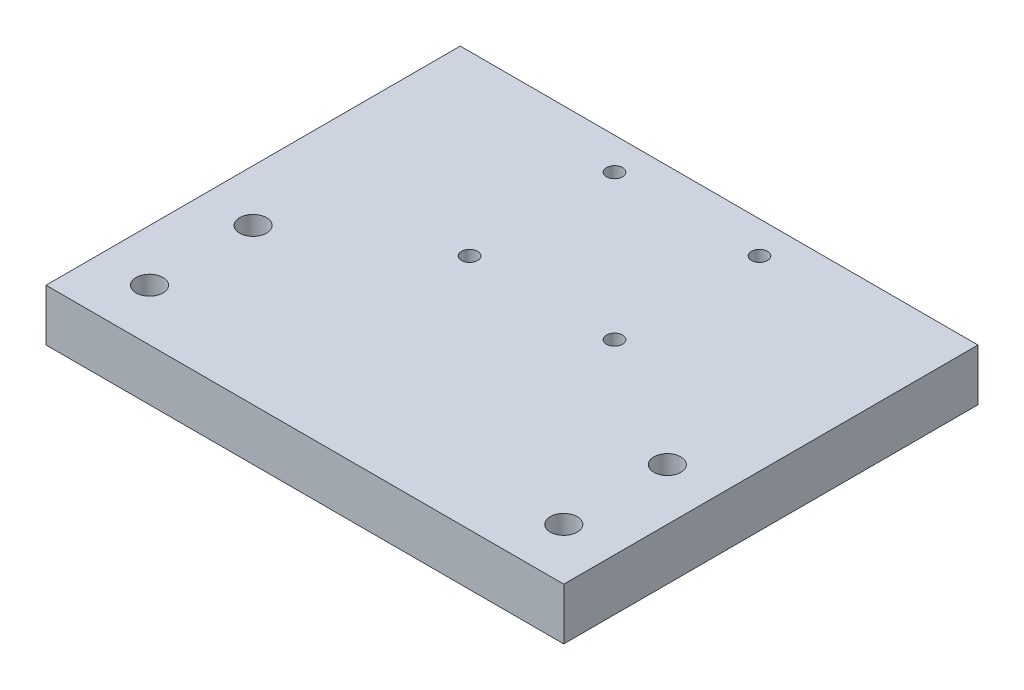
SolidWorks part; units mm, degrees
ref_plane "前视基准面" through (0, 0, 0) normal (0, 0, 1) x (1, 0, 0)
ref_plane "上视基准面" through (0, 0, 0) normal (0, 1, 0) x (1, 0, 0)
ref_plane "右视基准面" through (0, 0, 0) normal (1, 0, 0) x (0, 0, -1)
other "Configuration Table"
sketch "草图1" plane through (0, 0, 0) normal (0, 1, 0) x (1, 0, 0)
  line L1 (-50, 40) -> (50, 40)
  line L2 (-50, 40) -> (-50, -40)
  line L3 (-50, -40) -> (50, -40)
  line L4 (50, 40) -> (50, -40)
  line L5 (-50, 40) -> (50, -40) construction
  line L6 (-50, -40) -> (50, 40) construction
  point P0 (0, 0)
  dimension "D1" = 80
  dimension "D2" = 100
extrude "凸台-拉伸1" add sketch "草图1" along normal blind 10
sketch "草图3" plane through (0, 0, 0) normal (0, -1, 0) x (1, 0, 0)
  circle A0 centre (40, 30) radius 2.6
  circle A1 centre (40, 10) radius 2.6
  circle A2 centre (-40, 30) radius 2.6
  circle A3 centre (-40, 10) radius 2.6
  dimension "D1" = 5.2
  dimension "D2" = 5.2
  dimension "D3" = 5.2
  dimension "D4" = 5.2
extrude "切除-拉伸2" cut sketch "草图3" against normal through all
cosmetic thread "装饰螺纹线1" parameters "D1"=10, "D2"=6.2
cosmetic thread "装饰螺纹线2" parameters "D1"=10, "D2"=6.2
cosmetic thread "装饰螺纹线3" parameters "D1"=10, "D2"=6.2
cosmetic thread "装饰螺纹线4" parameters "D1"=10, "D2"=6.2
sketch "草图4" plane through (0, 10, 0) normal (0, 1, 0) x (1, 0, 0)
  circle A0 centre (14, 33.8) radius 1.55
  circle A1 centre (14, 5.8) radius 1.55
  circle A2 centre (-14, 33.8) radius 1.55
  circle A3 centre (-14, 5.8) radius 1.55
  dimension "D1" = 3.1
  dimension "D2" = 3.1
  dimension "D3" = 3.1
  dimension "D4" = 3.1
extrude "切除-拉伸3" cut sketch "草图4" against normal through all
